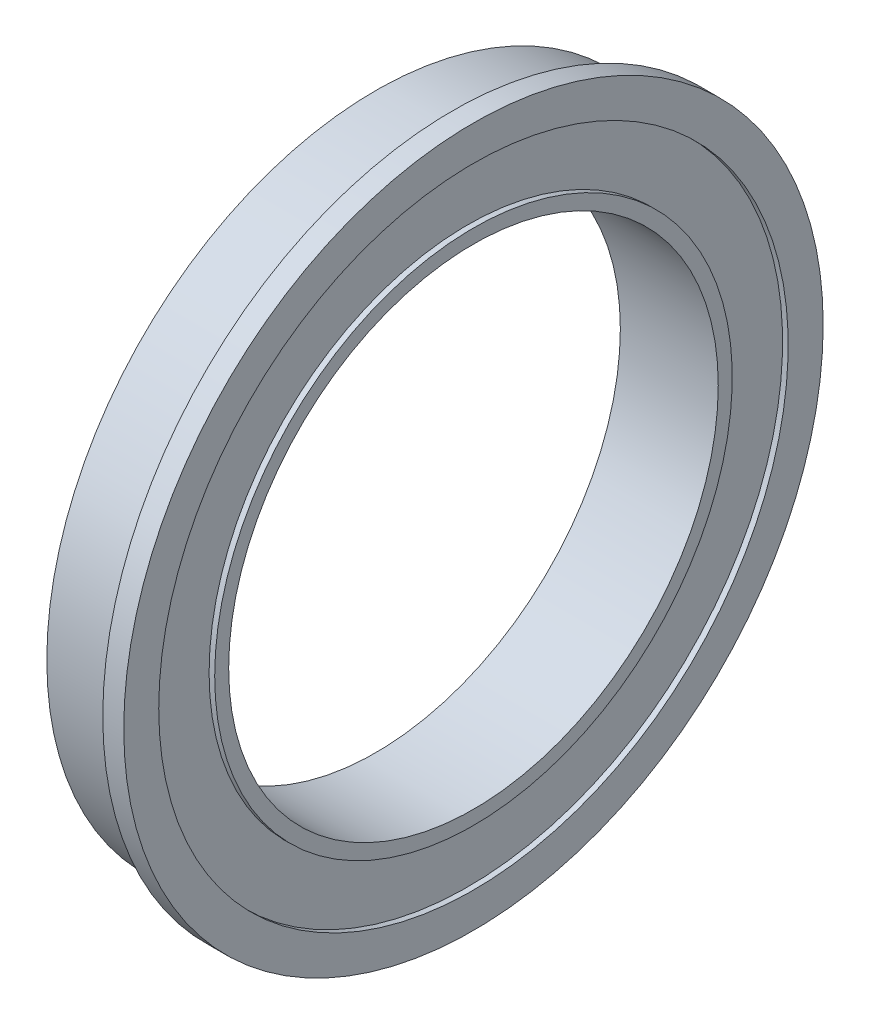
SolidWorks part; units mm, degrees
material "AISI 304"
ref_plane "前视基准面" through (0, 0, 0) normal (0, 0, 1) x (1, 0, 0)
ref_plane "上视基准面" through (0, 0, 0) normal (0, 1, 0) x (1, 0, 0)
ref_plane "右视基准面" through (0, 0, 0) normal (1, 0, 0) x (0, 0, -1)
sketch "草图1" plane through (0, 0, 0) normal (0, 0, 1) x (1, 0, 0)
  line L0 (5.5, 25) -> (7, 25)
  line L1 (7, 25) -> (7, 22.5)
  line L2 (7, 22.5) -> (6.6, 22.5)
  line L3 (6.6, 22.5) -> (6.6, 18.5)
  line L4 (6.6, 18.5) -> (7, 18.5)
  line L5 (7, 18.5) -> (7, 17.5)
  line L6 (7, 17.5) -> (0, 17.5)
  line L7 (0, 17.5) -> (0, 18.5)
  line L8 (0, 18.5) -> (0.4, 18.5)
  line L9 (0.4, 18.5) -> (0.4, 22.5)
  line L10 (0.4, 22.5) -> (0, 22.5)
  line L11 (0, 22.5) -> (0, 23.5)
  line L12 (0, 23.5) -> (5.5, 23.5)
  line L13 (5.5, 23.5) -> (5.5, 25)
  line L14 (0, 0) -> (9.7391, 0) construction
  dimension "D1" = 0.4
  dimension "D2" = 0.4
  dimension "D3" = 1.5
  dimension "D4" = 7
  dimension "D5" = 35
  dimension "D6" = 47
  dimension "D7" = 50
  dimension "D8" = 1
  dimension "D9" = 4
revolve "旋转1" add sketch "草图1" angle 360 about L14
